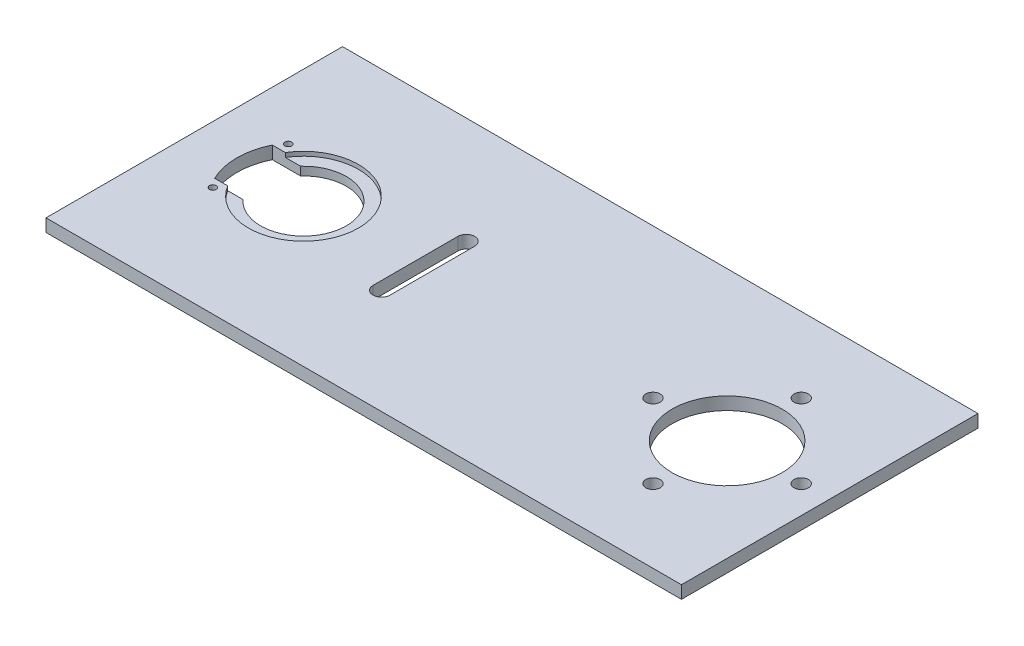
SolidWorks part; units mm, degrees
ref_plane "Front" through (0, 0, 0) normal (0, 0, 1) x (1, 0, 0)
ref_plane "Top" through (0, 0, 0) normal (0, 1, 0) x (1, 0, 0)
ref_plane "Right" through (0, 0, 0) normal (1, 0, 0) x (0, 0, -1)
sketch "Sketch1" plane through (0, 0, 0) normal (0, 1, 0) x (1, 0, 0)
  line L1 (0, 0) -> (150, 0)
  line L2 (0, 0) -> (0, 70)
  line L3 (0, 70) -> (150, 70)
  line L4 (150, 0) -> (150, 70)
  dimension "D1" = 70
  dimension "D2" = 150
extrude "Boss-Extrude1" add sketch "Sketch1" along normal blind 3
sketch "Sketch2" plane through (0, 3, 0) normal (0, 1, 0) x (1, 0, 0)
  line L0 (25.9788, 34.7957) -> (125.9788, 34.7957) construction
  line L1 (54.4042, 44.7957) -> (54.4042, 24.7957) construction
  line L2 (56.4042, 44.7957) -> (56.4042, 24.7957)
  line L3 (52.4042, 44.7957) -> (52.4042, 24.7957)
  line L4 (18.4988, 41.5957) -> (11.828, 41.5957)
  line L5 (18.4988, 41.5957) -> (18.4988, 27.9957) construction
  line L9 (18.4988, 27.9957) -> (11.828, 27.9957)
  line L11 (44.7063, 70) -> (44.7063, 0) construction
  line L12 (150, 70) -> (0, 70) construction
  line L13 (18.4988, 27.9957) -> (18.4988, 41.5957) construction
  line L14 (0, 0) -> (150, 0) construction
  circle A1 centre (125.9788, 34.7957) radius 13
  arc A2 (56.4042, 44.7957) -> (52.4042, 44.7957) centre (54.4042, 44.7957) ccw
  arc A3 (52.4042, 24.7957) -> (56.4042, 24.7957) centre (54.4042, 24.7957) ccw
  circle A4 centre (125.9788, 34.7957) radius 6 construction
  arc A10 (11.828, 41.5957) -> (11.828, 27.9957) centre (25.7568, 34.7957) ccw
  arc A11 (18.4988, 27.9957) -> (18.4988, 41.5957) centre (25.9788, 34.7957) ccw
  circle A12 centre (13.4988, 43.6957) radius 0.8
  circle A13 centre (13.4988, 25.8957) radius 0.8
  point P5 (54.4042, 34.7957)
  point P11 (68.3952, 34.7957)
  point P19 (54.4042, 34.7957)
  dimension "D1" = 15.5
  dimension "D2" = 26
  dimension "D5" = 2
  dimension "D3" = 1.6
  dimension "D11" = 10.1089
  dimension "D4" = 20
  dimension "D6" = 2.1
  dimension "D7" = 5
  dimension "D10" = 6.6707
  dimension "D12" = 7.48
extrude "Cut-Extrude1" cut sketch "Sketch2" against normal through all
sketch "Sketch3" plane through (0, 3, 0) normal (0, 1, 0) x (1, 0, 0)
  circle A0 centre (25.9788, 34.7957) radius 13
  dimension "D1" = 26
extrude "Cut-Extrude2" cut sketch "Sketch3" against normal blind 1
hole_wizard "M3 Clearance Hole1" positions "Sketch4" profile "Sketch5" hole size "M3" standard "ISO"
sketch "Sketch4" plane through (0, 3, 0) normal (0, 1, 0) x (1, 0, 0)
  circle A0 centre (125.9788, 34.7957) radius 17.5 construction
  point P5 (125.9788, 52.2957)
  point P7 (108.4788, 34.7957)
  point P9 (125.9788, 17.2957)
  point P11 (143.4788, 34.7957)
  dimension "D1" = 35
sketch "Sketch5" plane through (143.4788, 3, -34.7957) normal (1, 0, 0) x (0, 0, 1)
  line L0 (0, 0) -> (0, 8.0215)
  line L1 (0, 8.0215) -> (1.7, 7)
  line L2 (1.7, 7) -> (1.7, 0)
  line L5 (1.7, 0) -> (0, 0)
  line L10 (0, 8.0215) -> (-1.7, 7) construction
  line L11 (0, -6.35) -> (0, 107.95) construction
  dimension "Hole Dia." = 3.4
  dimension "Hole Depth" = 7
  dimension "Drill Angle" = 118
